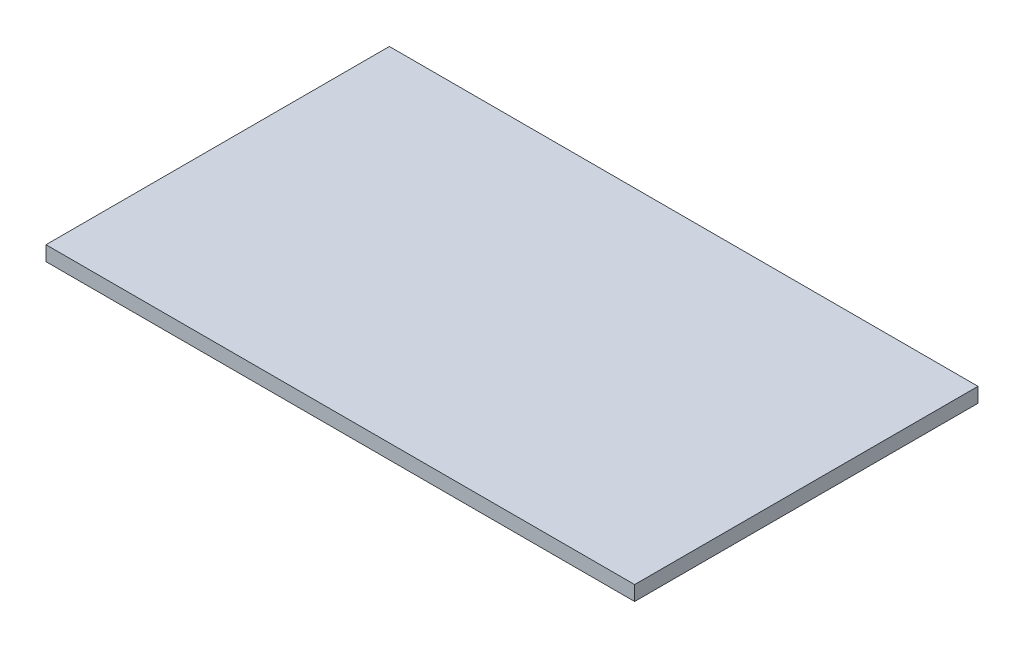
SolidWorks part; units mm, degrees
ref_plane "Front Plane" through (0, 0, 0) normal (0, 0, 1) x (1, 0, 0)
ref_plane "Top Plane" through (0, 0, 0) normal (0, 1, 0) x (1, 0, 0)
ref_plane "Right Plane" through (0, 0, 0) normal (1, 0, 0) x (0, 0, -1)
sketch "Sketch2" plane through (0, 0, 0) normal (0, 1, 0) x (1, 0, 0)
  line L1 (0, 0) -> (120, 0)
  line L2 (0, 0) -> (0, 70)
  line L3 (0, 70) -> (120, 70)
  line L4 (120, 0) -> (120, 70)
extrude "Boss-Extrude1" add sketch "Sketch2" along normal blind 3
